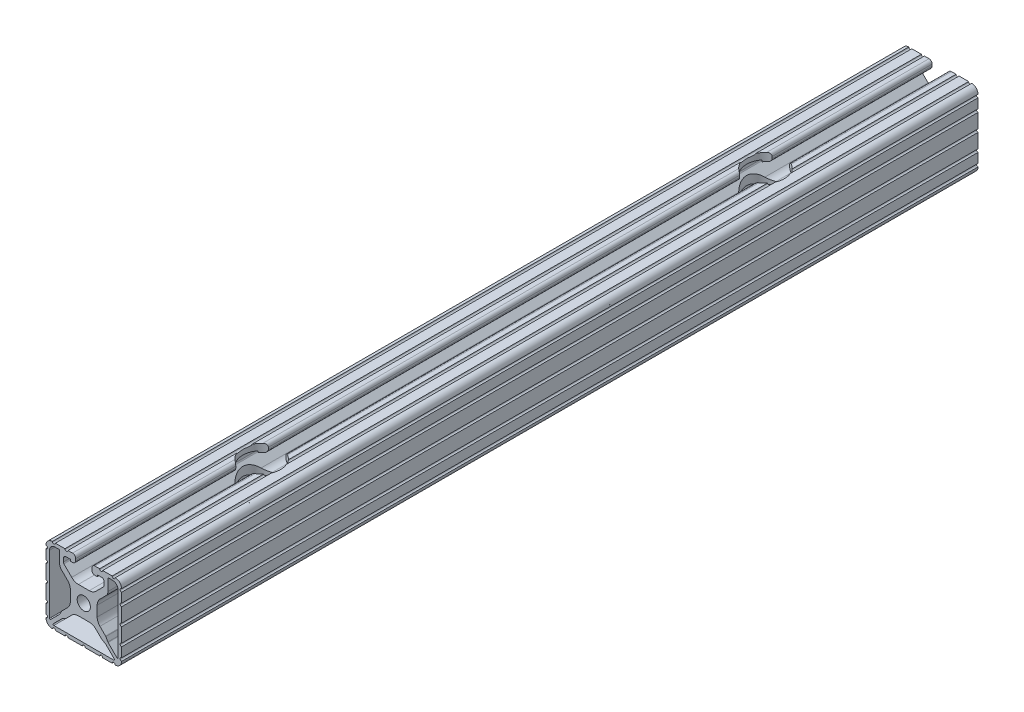
SolidWorks part; units mm, degrees
material "6105-T5 Aluminum"
ref_plane "Front Plane" through (0, 0, 0) normal (0, 0, 1) x (1, 0, 0)
ref_plane "Top Plane" through (0, 0, 0) normal (0, 1, 0) x (1, 0, 0)
ref_plane "Right Plane" through (0, 0, 0) normal (1, 0, 0) x (0, 0, -1)
sketch "Sketch1" plane through (0, 0, 0) normal (0, 0, 1) x (1, 0, 0)
  line L0 (17.272, -15.1936) -> (17.272, 14.478)
  line L1 (12.2663, -11.0145) -> (16.6875, -15.4357)
  line L2 (11.1044, -8.9951) -> (12.14, -10.8475)
  line L3 (8.1475, -5.9974) -> (10.9781, -8.8281)
  line L4 (6.7564, 2.525) -> (6.7564, -2.6388)
  line L5 (11.2435, 8.979) -> (8.1479, 5.8839)
  line L6 (12.1736, 16.891) -> (12.1736, 11.2243)
  line L7 (14.478, 17.272) -> (12.5546, 17.272)
  line L8 (-12.1736, 11.2243) -> (-12.1736, 16.891)
  line L9 (-8.1479, 5.8839) -> (-11.2435, 8.979)
  line L10 (-6.7564, -2.6388) -> (-6.7564, 2.525)
  line L11 (-10.9781, -8.8281) -> (-8.1475, -5.9974)
  line L12 (-12.14, -10.8475) -> (-11.1044, -8.9951)
  line L13 (-16.6875, -15.4357) -> (-12.2663, -11.0145)
  line L14 (-17.272, 14.478) -> (-17.272, -15.1936)
  line L15 (-12.5546, 17.272) -> (-14.478, 17.272)
  line L16 (15.3589, -16.6216) -> (11.091, -12.3537)
  line L17 (-15.0895, -17.272) -> (15.0895, -17.272)
  line L18 (-11.091, -12.3537) -> (-15.3589, -16.6216)
  line L19 (-9.0722, -11.1921) -> (-10.924, -12.2274)
  line L20 (-6.1016, -8.262) -> (-8.9052, -11.0658)
  line L21 (2.7429, -6.8707) -> (-2.7429, -6.8707)
  line L22 (8.9052, -11.0658) -> (6.1016, -8.262)
  line L23 (10.924, -12.2274) -> (9.0722, -11.1921)
  line L24 (6.8141, 15.8247) -> (9.017, 15.8247)
  line L25 (10.287, 14.5547) -> (10.287, 12.8154)
  line L26 (10.0266, 12.1868) -> (6.1008, 8.2616)
  line L27 (2.7424, 6.8707) -> (-2.7424, 6.8707)
  line L28 (-6.1008, 8.2616) -> (-10.0266, 12.1868)
  line L29 (-10.287, 12.8154) -> (-10.287, 14.5547)
  line L30 (-9.017, 15.8247) -> (-6.8141, 15.8247)
  line L31 (-6.8141, 15.8247) -> (-6.8141, 14.986)
  line L32 (-6.8141, 14.986) -> (-5.6388, 14.986)
  line L33 (-4.064, 16.5608) -> (-4.064, 17.4752)
  line L34 (-5.6388, 19.05) -> (-7.9756, 19.05)
  line L35 (-9.4996, 19.05) -> (-14.3256, 19.05)
  line L36 (-15.8496, 19.05) -> (-15.875, 19.05)
  line L37 (-19.05, 15.875) -> (-19.05, 15.8496)
  line L38 (-19.05, 14.3256) -> (-19.05, 9.4996)
  line L39 (-19.05, 7.9756) -> (-19.05, 0.762)
  line L40 (-19.05, -0.762) -> (-19.05, -7.9756)
  line L41 (-19.05, -9.4996) -> (-19.05, -14.3256)
  line L42 (-19.05, -15.8496) -> (-19.05, -15.875)
  line L43 (-15.875, -19.05) -> (-15.8496, -19.05)
  line L44 (-14.3256, -19.05) -> (-9.4996, -19.05)
  line L45 (-7.9756, -19.05) -> (-0.762, -19.05)
  line L46 (0.762, -19.05) -> (7.9756, -19.05)
  line L47 (9.4996, -19.05) -> (14.3256, -19.05)
  line L48 (15.8496, -19.05) -> (15.875, -19.05)
  line L49 (19.05, -15.875) -> (19.05, -15.8496)
  line L50 (19.05, -14.3256) -> (19.05, -9.4996)
  line L51 (19.05, -7.9756) -> (19.05, -0.762)
  line L52 (19.05, 0.762) -> (19.05, 7.9756)
  line L53 (19.05, 9.4996) -> (19.05, 14.3256)
  line L54 (19.05, 15.8496) -> (19.05, 15.875)
  line L55 (15.875, 19.05) -> (15.8496, 19.05)
  line L56 (14.3256, 19.05) -> (9.4996, 19.05)
  line L57 (7.9756, 19.05) -> (5.6388, 19.05)
  line L58 (4.064, 17.4752) -> (4.064, 16.5608)
  line L59 (5.6388, 14.986) -> (6.8141, 14.986)
  line L60 (6.8141, 14.986) -> (6.8141, 15.8247)
  circle A0 centre (0, 0) radius 3.3274
  arc A1 (17.272, 14.478) -> (14.478, 17.272) centre (14.478, 14.478) ccw
  arc A2 (16.6875, -15.4357) -> (17.272, -15.1936) centre (16.9296, -15.1936) ccw
  arc A3 (12.14, -10.8475) -> (12.2663, -11.0145) centre (12.8051, -10.4757) ccw
  arc A4 (11.1044, -8.9951) -> (10.9781, -8.8281) centre (10.4393, -9.3669) ccw
  arc A5 (6.7564, -2.6388) -> (8.1475, -5.9974) centre (11.5062, -2.6388) ccw
  arc A6 (8.1479, 5.8839) -> (6.7564, 2.525) centre (11.5062, 2.525) ccw
  arc A7 (11.2435, 8.979) -> (12.1736, 11.2243) centre (8.9986, 11.2243) ccw
  arc A8 (12.5546, 17.272) -> (12.1736, 16.891) centre (12.5546, 16.891) ccw
  arc A9 (-12.1736, 16.891) -> (-12.5546, 17.272) centre (-12.5546, 16.891) ccw
  arc A10 (-12.1736, 11.2243) -> (-11.2435, 8.979) centre (-8.9986, 11.2243) ccw
  arc A11 (-6.7564, 2.525) -> (-8.1479, 5.8839) centre (-11.5062, 2.525) ccw
  arc A12 (-8.1475, -5.9974) -> (-6.7564, -2.6388) centre (-11.5062, -2.6388) ccw
  arc A13 (-10.9781, -8.8281) -> (-11.1044, -8.9951) centre (-10.4393, -9.3669) ccw
  arc A14 (-12.2663, -11.0145) -> (-12.14, -10.8475) centre (-12.8051, -10.4757) ccw
  arc A15 (-17.272, -15.1936) -> (-16.6875, -15.4357) centre (-16.9296, -15.1936) ccw
  arc A16 (-14.478, 17.272) -> (-17.272, 14.478) centre (-14.478, 14.478) ccw
  arc A17 (11.091, -12.3537) -> (10.924, -12.2274) centre (10.5522, -12.8925) ccw
  arc A18 (15.0895, -17.272) -> (15.3589, -16.6216) centre (15.0895, -16.891) ccw
  arc A19 (-15.3589, -16.6216) -> (-15.0895, -17.272) centre (-15.0895, -16.891) ccw
  arc A20 (-10.924, -12.2274) -> (-11.091, -12.3537) centre (-10.5522, -12.8925) ccw
  arc A21 (-9.0722, -11.1921) -> (-8.9052, -11.0658) centre (-9.4441, -10.527) ccw
  arc A22 (-2.7429, -6.8707) -> (-6.1016, -8.262) centre (-2.7429, -11.6205) ccw
  arc A23 (6.1016, -8.262) -> (2.7429, -6.8707) centre (2.7429, -11.6205) ccw
  arc A24 (8.9052, -11.0658) -> (9.0722, -11.1921) centre (9.4441, -10.527) ccw
  arc A25 (10.287, 14.5547) -> (9.017, 15.8247) centre (9.017, 14.5547) ccw
  arc A26 (10.0266, 12.1868) -> (10.287, 12.8154) centre (9.398, 12.8154) ccw
  arc A27 (2.7424, 6.8707) -> (6.1008, 8.2616) centre (2.7424, 11.6205) ccw
  arc A28 (-6.1008, 8.2616) -> (-2.7424, 6.8707) centre (-2.7424, 11.6205) ccw
  arc A29 (-10.287, 12.8154) -> (-10.0266, 12.1868) centre (-9.398, 12.8154) ccw
  arc A30 (-9.017, 15.8247) -> (-10.287, 14.5547) centre (-9.017, 14.5547) ccw
  arc A31 (-5.6388, 14.986) -> (-4.064, 16.5608) centre (-5.6388, 16.5608) ccw
  arc A32 (-4.064, 17.4752) -> (-5.6388, 19.05) centre (-5.6388, 17.4752) ccw
  arc A33 (-9.4996, 19.05) -> (-7.9756, 19.05) centre (-8.7376, 19.05) ccw
  arc A34 (-15.8496, 19.05) -> (-14.3256, 19.05) centre (-15.0876, 19.05) ccw
  arc A35 (-15.875, 19.05) -> (-19.05, 15.875) centre (-15.875, 15.875) ccw
  arc A36 (-19.05, 14.3256) -> (-19.05, 15.8496) centre (-19.05, 15.0876) ccw
  arc A37 (-19.05, 7.9756) -> (-19.05, 9.4996) centre (-19.05, 8.7376) ccw
  arc A38 (-19.05, -0.762) -> (-19.05, 0.762) centre (-19.05, 0) ccw
  arc A39 (-19.05, -9.4996) -> (-19.05, -7.9756) centre (-19.05, -8.7376) ccw
  arc A40 (-19.05, -15.8496) -> (-19.05, -14.3256) centre (-19.05, -15.0876) ccw
  arc A41 (-19.05, -15.875) -> (-15.875, -19.05) centre (-15.875, -15.875) ccw
  arc A42 (-14.3256, -19.05) -> (-15.8496, -19.05) centre (-15.0876, -19.05) ccw
  arc A43 (-7.9756, -19.05) -> (-9.4996, -19.05) centre (-8.7376, -19.05) ccw
  arc A44 (0.762, -19.05) -> (-0.762, -19.05) centre (0, -19.05) ccw
  arc A45 (9.4996, -19.05) -> (7.9756, -19.05) centre (8.7376, -19.05) ccw
  arc A46 (15.8496, -19.05) -> (14.3256, -19.05) centre (15.0876, -19.05) ccw
  arc A47 (15.875, -19.05) -> (19.05, -15.875) centre (15.875, -15.875) ccw
  arc A48 (19.05, -14.3256) -> (19.05, -15.8496) centre (19.05, -15.0876) ccw
  arc A49 (19.05, -7.9756) -> (19.05, -9.4996) centre (19.05, -8.7376) ccw
  arc A50 (19.05, 0.762) -> (19.05, -0.762) centre (19.05, 0) ccw
  arc A51 (19.05, 9.4996) -> (19.05, 7.9756) centre (19.05, 8.7376) ccw
  arc A52 (19.05, 15.8496) -> (19.05, 14.3256) centre (19.05, 15.0876) ccw
  arc A53 (19.05, 15.875) -> (15.875, 19.05) centre (15.875, 15.875) ccw
  arc A54 (14.3256, 19.05) -> (15.8496, 19.05) centre (15.0876, 19.05) ccw
  arc A55 (7.9756, 19.05) -> (9.4996, 19.05) centre (8.7376, 19.05) ccw
  arc A56 (5.6388, 19.05) -> (4.064, 17.4752) centre (5.6388, 17.4752) ccw
  arc A57 (4.064, 16.5608) -> (5.6388, 14.986) centre (5.6388, 16.5608) ccw
extrude "Extrude1" add sketch "Sketch1" against normal blind 431.8
sketch "Sketch2" plane through (0, -19.05, 0) normal (0, -1, 0) x (1, 0, 0)
  line L0 (0.762, -431.8) -> (0.762, 0) construction
  line L1 (-19.05, -215.9) -> (19.05, -215.9) construction
  line L2 (-19.05, -431.8) -> (-19.05, 0) construction
  line L3 (19.05, -431.8) -> (19.05, 0) construction
  circle A0 centre (0.762, -88.9) radius 9.525
  circle A1 centre (0.762, -342.9) radius 9.525
  dimension "D3" = 19.05
  dimension "D1" = 127
  dimension "D2" = 254
extrude "Cut-Extrude1" cut sketch "Sketch2" against normal through all
